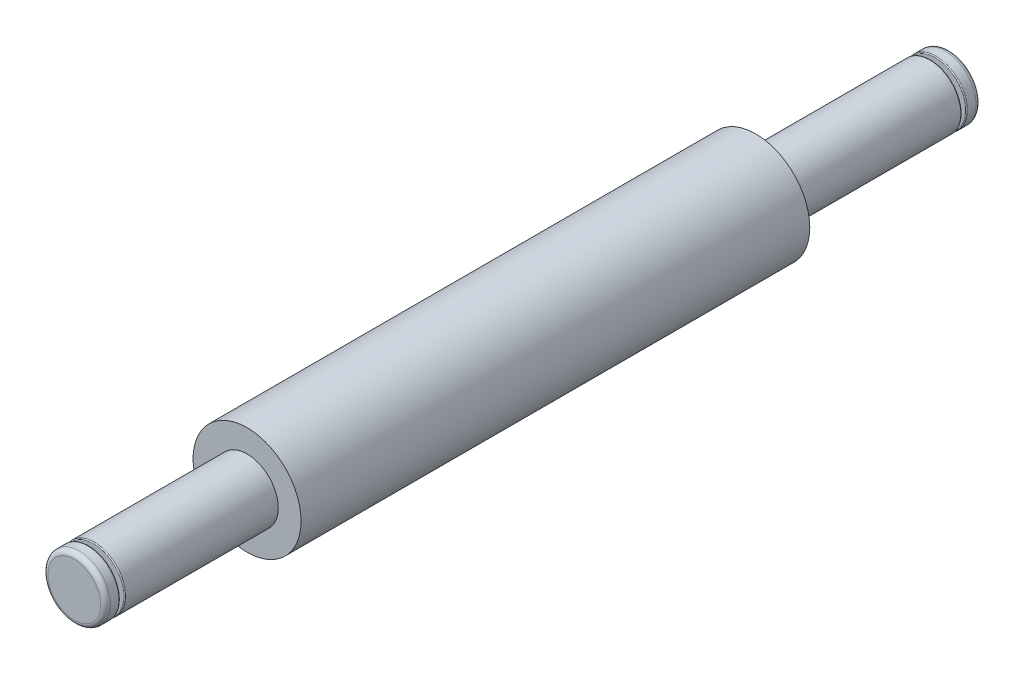
SolidWorks part; units mm, degrees
ref_plane "Front Plane" through (0, 0, 0) normal (0, 0, 1) x (1, 0, 0)
ref_plane "Top Plane" through (0, 0, 0) normal (0, 1, 0) x (1, 0, 0)
ref_plane "Right Plane" through (0, 0, 0) normal (1, 0, 0) x (0, 0, -1)
sketch "Sketch1" plane through (0, 0, 0) normal (0, 0, 1) x (1, 0, 0)
  circle A1 centre (-222.1854, 59.6173) radius 5.625
extrude "Boss-Extrude1" add sketch "Sketch1" against normal blind 53
sketch "Sketch2" plane through (0, 0, 0) normal (0, 0, 1) x (1, 0, 0)
  circle A0 centre (-222.1854, 59.6173) radius 3.25
  dimension "D1" = 6.5
extrude "Boss-Extrude2" add sketch "Sketch2" along normal blind 16 and the other way blind 71.2
sketch "Sketch3" plane through (0, 0, 16) normal (0, 0, 1) x (1, 0, 0)
  circle A0 centre (-222.1854, 59.6173) radius 1.75
  dimension "D1" = 3.5
extrude "Boss-Extrude3" add sketch "Sketch3" along normal blind 0.5
sketch "Sketch4" plane through (0, 0, -71.2) normal (0, 0, -1) x (-1, 0, 0)
  circle A0 centre (222.1854, 59.6173) radius 1.75
  dimension "D1" = 3.5
extrude "Boss-Extrude4" add sketch "Sketch4" along normal blind 0.5
sketch "Sketch5" plane through (0, 0, -71.7) normal (0, 0, -1) x (-1, 0, 0)
  circle A0 centre (222.1854, 59.6173) radius 3.25
extrude "Boss-Extrude5" add sketch "Sketch5" along normal blind 1.5
sketch "Sketch6" plane through (0, 0, 16.5) normal (0, 0, 1) x (1, 0, 0)
  circle A0 centre (-222.1854, 59.6173) radius 3.25
  dimension "D1" = 6.5
extrude "Boss-Extrude6" add sketch "Sketch6" along normal blind 1.5
fillet "Fillet1" radius 0.1 4 edges at (-218.9354, 59.6173, -71.2) (-225.4354, 59.6173, -71.7) (-218.9354, 59.6173, 16.5) (-218.9354, 59.6173, 16)
fillet "Fillet2" radius 0.5 2 edges at (-218.9354, 59.6173, 18) (-225.4354, 59.6173, -73.2)
